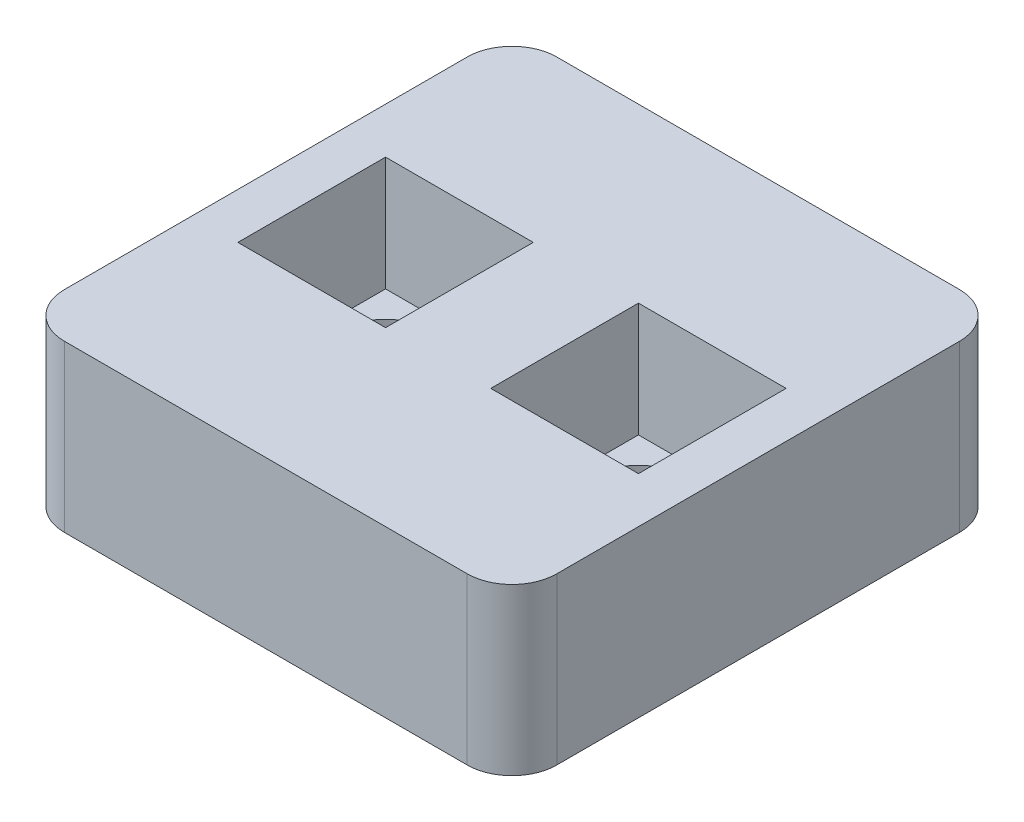
SolidWorks part; units mm, degrees
ref_plane "Front Plane" through (0, 0, 0) normal (0, 0, 1) x (1, 0, 0)
ref_plane "Top Plane" through (0, 0, 0) normal (0, 1, 0) x (1, 0, 0)
ref_plane "Right Plane" through (0, 0, 0) normal (1, 0, 0) x (0, 0, -1)
sketch "Sketch1" plane through (0, 0, 0) normal (0, 1, 0) x (1, 0, 0)
  line L1 (-5.5, -5.5) -> (5.5, -5.5)
  line L2 (-5.5, -5.5) -> (-5.5, 5.5)
  line L3 (-5.5, 5.5) -> (5.5, 5.5)
  line L4 (5.5, -5.5) -> (5.5, 5.5)
  line L5 (-5.5, -5.5) -> (5.5, 5.5) construction
  line L6 (-5.5, 5.5) -> (5.5, -5.5) construction
  point P0 (0, 0)
  dimension "D1" = 11
  dimension "D2" = 11
extrude "Boss-Extrude1" add sketch "Sketch1" along normal blind 3.7
fillet "Fillet1" radius 1 4 edges at (-5.5, 1.85, -5.5) (-5.5, 1.85, 5.5) (5.5, 1.85, -5.5) (5.5, 1.85, 5.5)
sketch "Sketch2" plane through (0, 3.7, 0) normal (0, 1, 0) x (1, 0, 0)
  line L0 (-2.825, 0) -> (2.825, 0) construction
  line L2 (-4.475, -1.65) -> (-1.175, -1.65)
  line L3 (-4.475, -1.65) -> (-4.475, 1.65)
  line L4 (-4.475, 1.65) -> (-1.175, 1.65)
  line L5 (-1.175, -1.65) -> (-1.175, 1.65)
  line L6 (-4.475, -1.65) -> (-1.175, 1.65) construction
  line L7 (-4.475, 1.65) -> (-1.175, -1.65) construction
  line L8 (1.175, -1.65) -> (4.475, -1.65)
  line L9 (1.175, -1.65) -> (1.175, 1.65)
  line L10 (1.175, 1.65) -> (4.475, 1.65)
  line L11 (4.475, -1.65) -> (4.475, 1.65)
  line L12 (1.175, -1.65) -> (4.475, 1.65) construction
  line L13 (1.175, 1.65) -> (4.475, -1.65) construction
  point P4 (0, 0)
  dimension "D1" = 3.3
  dimension "D2" = 3.3
  dimension "D3" = 3.3
  dimension "D4" = 3.3
  dimension "D5" = 5.65
extrude "Cut-Extrude1" cut sketch "Sketch2" against normal blind 2.55
sketch "Sketch4" plane through (0, 0, 0) normal (0, -1, 0) x (-1, 0, 0)
  line L0 (2.825, 0) -> (-2.825, 0) construction
  circle A0 centre (2.825, 0) radius 2.2
  circle A1 centre (-2.825, 0) radius 2.2
  point P8 (0, 0)
  dimension "D1" = 5.65
  dimension "D2" = 4.4
  dimension "D3" = 4.4
extrude "Boss-Extrude2" [suppressed] add sketch "Sketch4" along normal blind 2
sketch "Sketch5" [suppressed] plane through (0, -2, 0) normal (0, -1, 0) x (-1, 0, 0)
  line L1 (9.5, 10.5) -> (-9.5, 10.5)
  line L2 (10.5, 9.5) -> (10.5, -9.5)
  line L3 (9.5, -10.5) -> (-9.5, -10.5)
  line L4 (-10.5, 9.5) -> (-10.5, -9.5)
  line L5 (10.5, 10.5) -> (-10.5, -10.5) construction
  line L6 (10.5, -10.5) -> (-10.5, 10.5) construction
  arc A0 (10.5, -9.5) -> (9.5, -10.5) centre (9.5, -9.5) cw
  arc A1 (-10.5, -9.5) -> (-9.5, -10.5) centre (-9.5, -9.5) ccw
  arc A2 (-9.5, 10.5) -> (-10.5, 9.5) centre (-9.5, 9.5) ccw
  arc A3 (9.5, 10.5) -> (10.5, 9.5) centre (9.5, 9.5) cw
  point P0 (0, 0)
  dimension "D3" = 1
  dimension "D1" = 21
  dimension "D2" = 21
extrude "Boss-Extrude3" [suppressed] add sketch "Sketch5" against normal blind 2
sketch "Sketch3" plane through (0, 3.7, 0) normal (0, 1, 0) x (1, 0, 0)
  line L0 (-2.825, 0) -> (2.825, 0) construction
  circle A0 centre (-2.825, 0) radius 1.5
  circle A1 centre (2.825, 0) radius 1.5
  point P8 (0, 0)
  dimension "D2" = 3
  dimension "D3" = 3
  dimension "D1" = 5.65
extrude "Cut-Extrude2" cut sketch "Sketch3" against normal through all
sketch "Sketch7" [suppressed] plane through (0, 0, 0) normal (0, 1, 0) x (1, 0, 0)
  line L0 (9.5, -10.5) -> (-9.5, -10.5) construction
  line L1 (2.8284, -14.7426) -> (4.2426, -13.3284)
  line L2 (2.8284, -14.7426) -> (-3.8891, -8.0251)
  line L3 (-3.8891, -7.318) -> (-3.182, -6.6109)
  line L4 (4.2426, -13.3284) -> (-2.4749, -6.6109)
  line L5 (2.8284, -14.7426) -> (-2.8284, -6.2574) construction
  line L6 (-4.2426, -7.6716) -> (4.2426, -13.3284) construction
  line L8 (-4.2426, -13.3284) -> (-2.8284, -14.7426)
  line L9 (-4.2426, -13.3284) -> (2.4749, -6.6109)
  line L10 (3.182, -6.6109) -> (3.8891, -7.318)
  line L11 (-2.8284, -14.7426) -> (3.8891, -8.0251)
  line L12 (-4.2426, -13.3284) -> (4.2426, -7.6716) construction
  line L13 (2.8284, -6.2574) -> (-2.8284, -14.7426) construction
  arc A0 (-2.4749, -6.6109) -> (-3.182, -6.6109) centre (-2.8284, -6.9645) ccw
  arc A1 (3.8891, -7.318) -> (3.8891, -8.0251) centre (3.5355, -7.6716) cw
  arc A2 (3.182, -6.6109) -> (2.4749, -6.6109) centre (2.8284, -6.9645) ccw
  arc A3 (-3.8891, -7.318) -> (-3.8891, -8.0251) centre (-3.5355, -7.6716) ccw
  point P0 (0, -10.5)
  point P7 (0, -10.5)
  point P12 (-1.4142, -10.5)
  point P13 (1.4142, -10.5)
  line M12 (-9.5, -10.5) -> (9.5, -10.5)
  dimension "D7" = 0.5
  dimension "D8" = 0.5
  dimension "D1" = 2
  dimension "D2" = 45
  dimension "D3" = 2
  dimension "D4" = 45
  dimension "D5" = 4
  dimension "D6" = 4
extrude "Cut-Extrude3" [suppressed] cut sketch "Sketch7" against normal through all contours L10 A2 L9 L4 L11 A1 | L3 A3 L2 L9 L4 A0 | L9 L4 M12
equation "\"D2@Sketch2\"=\"D1@Sketch2\""
equation "\"D3@Sketch2\"=\"D1@Sketch2\""
equation "\"D4@Sketch2\"=\"D1@Sketch2\""
equation "\"D2@Sketch1\"=\"D1@Sketch1\""
equation "\"D3@Sketch3\"=\"D2@Sketch3\""
equation "\"D3@Sketch4\"=\"D2@Sketch4\""
equation "\"D2@Sketch5\"=\"D1@Sketch5\""
equation "\"D3@Sketch7\"=\"D1@Sketch7\""
equation "\"D6@Sketch7\"=\"D5@Sketch7\""
